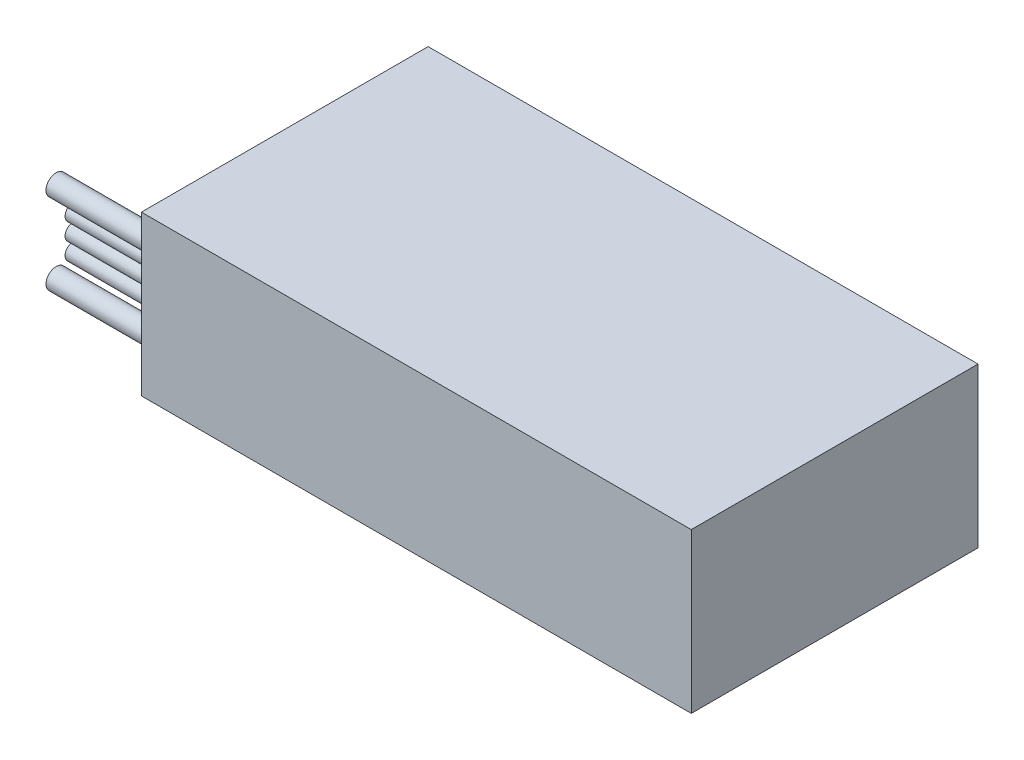
SolidWorks part; units mm, degrees
ref_plane "Front Plane" through (0, 0, 0) normal (0, 0, 1) x (1, 0, 0)
ref_plane "Top Plane" through (0, 0, 0) normal (0, 1, 0) x (1, 0, 0)
ref_plane "Right Plane" through (0, 0, 0) normal (1, 0, 0) x (0, 0, -1)
sketch "Sketch1" plane through (0, 0, 0) normal (0, 0, 1) x (1, 0, 0)
  line L1 (0, 0) -> (67.7, 0)
  line L2 (0, 0) -> (0, 19.6)
  line L3 (0, 19.6) -> (67.7, 19.6)
  line L4 (67.7, 0) -> (67.7, 19.6)
  dimension "D1" = 67.7
  dimension "D2" = 19.6
extrude "Boss-Extrude1" add sketch "Sketch1" along normal blind 35.3
sketch "Sketch3" plane through (0, 0, 0) normal (-1, 0, 0) x (0, 0, 1)
  line L0 (32.8, 14.8) -> (32.8, 4.8) construction
  line L1 (30.7, 8.75) -> (30.7, 6.65) construction
  line L2 (30.7, 8.75) -> (30.7, 10.85) construction
  line L3 (30.7, 10.85) -> (30.7, 12.95) construction
  line L4 (32.8, 9.8) -> (35.3, 9.8) construction
  line L5 (35.3, 19.6) -> (35.3, 0) construction
  line L6 (32.8, 9.8) -> (30.7, 9.8) construction
  circle A0 centre (30.7, 12.95) radius 1
  circle A1 centre (30.7, 10.85) radius 1
  circle A2 centre (30.7, 8.75) radius 1
  circle A3 centre (32.8, 4.8) radius 1.25
  circle A4 centre (32.8, 14.8) radius 1.25
  circle A5 centre (30.7, 6.65) radius 1
  dimension "D3" = 2
  dimension "D4" = 2.5
  dimension "D1" = 2.1
  dimension "D2" = 10
  dimension "D5" = 2.5
  dimension "D6" = 2.1
extrude "Boss-Extrude2" add sketch "Sketch3" along normal blind 13
